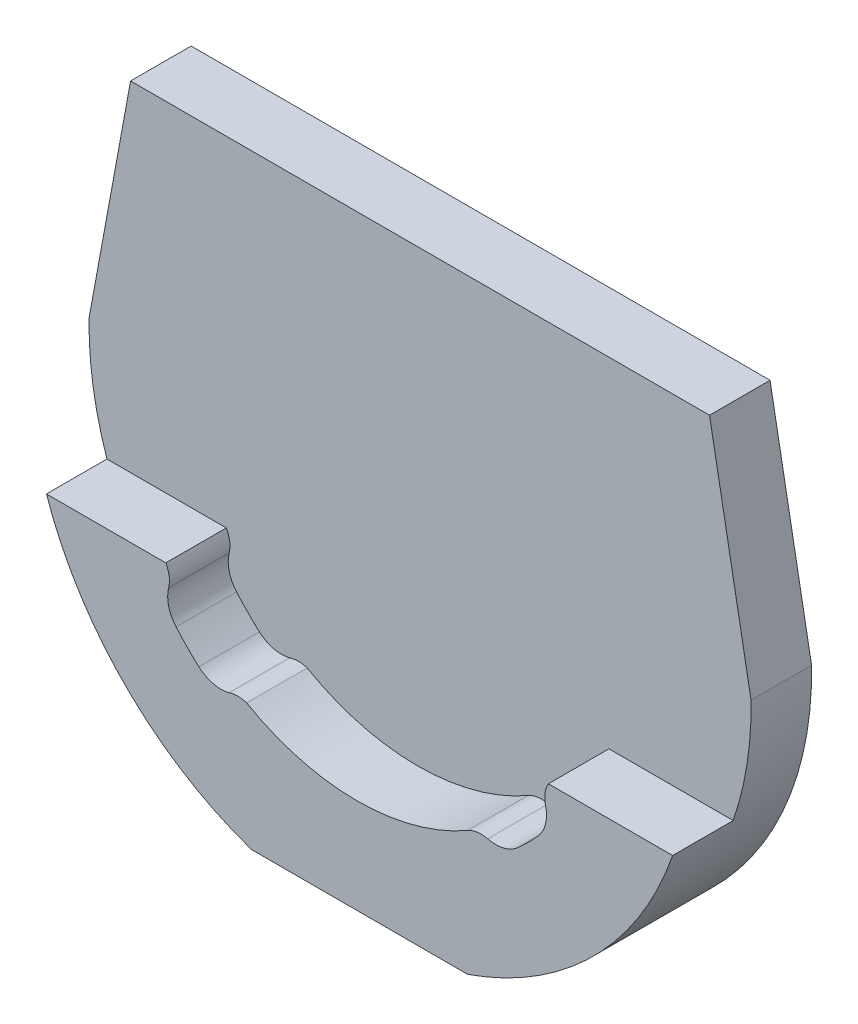
SolidWorks part; units mm, degrees
ref_plane "Front Plane" through (0, 0, 0) normal (0, 0, 1) x (1, 0, 0)
ref_plane "Top Plane" through (0, 0, 0) normal (0, 1, 0) x (1, 0, 0)
ref_plane "Right Plane" through (0, 0, 0) normal (1, 0, 0) x (0, 0, -1)
sketch "Sketch2" plane through (0, 0, 0) normal (0, 0, 1) x (1, 0, 0)
  line L0 (-34.0593, 56.9907) -> (-54.2651, -53.0408)
  line L1 (-24.0734, 56.0031) -> (-44.2734, -53.9969)
  line L2 (24.9266, 56.0031) -> (45.1266, -53.9969)
  line L3 (34.9124, 56.9907) -> (55.1182, -53.0408)
  line L7 (55.1182, -53.0408) -> (44.951, -53.0408)
  line L8 (-44.0979, -53.0408) -> (-54.2651, -53.0408)
  arc A0 (-44.2734, -53.9969) -> (45.1266, -53.9969) centre (0.4266, -53.9969) ccw
  arc A1 (24.9266, 56.0031) -> (-24.0734, 56.0031) centre (0.4266, 56.0031) ccw
  arc A2 (34.9124, 56.9907) -> (-34.0593, 56.9907) centre (0.4266, 56.0031) ccw
  arc A3 (-54.2651, -53.0408) -> (55.1182, -53.0408) centre (0.4266, -53.9969) ccw
extrude "Boss-Extrude1" add sketch "Sketch2" along normal blind 10 contours L2 A1 L1 A0 | L3 A2 L0 L8 L1 A1 L2 L7 | L8 A3 L7 L2 A0 L1
sketch "Sketch4" plane through (0, 0, 10) normal (0, 0, 1) x (1, 0, 0)
  line L1 (-70.8533, -127.1246) -> (76.5167, -127.1246)
  line L2 (-70.8533, -127.1246) -> (-70.8533, -105.6969)
  line L3 (-70.8533, -105.6969) -> (76.5167, -105.6969)
  line L4 (76.5167, -127.1246) -> (76.5167, -105.6969)
  arc A0 (-54.2651, -53.0408) -> (55.1182, -53.0408) centre (0.4266, -53.9969) ccw construction
  point P7 (0.4266, -108.6969)
  dimension "D1" = 3
extrude "Cut-Extrude1" cut sketch "Sketch4" against normal blind 10
sketch "Sketch5" plane through (0, 0, 10) normal (0, 0, 1) x (1, 0, 0)
  line L0 (0.4266, -105.6969) -> (0.4266, -15.6969) construction
  line L1 (18.2927, -105.6969) -> (-17.4396, -105.6969) construction
  line L3 (90.4458, -15.6969) -> (-88.3005, -15.6969)
  line L4 (90.4458, -15.6969) -> (90.4458, 96.6359)
  line L5 (90.4458, 96.6359) -> (-88.3005, 96.6359)
  line L6 (-88.3005, -15.6969) -> (-88.3005, 96.6359)
  dimension "D1" = 90
extrude "Cut-Extrude2" cut sketch "Sketch5" against normal blind 10
sketch "Sketch7" plane through (0, 0, 10) normal (0, 0, 1) x (1, 0, 0)
  line L0 (0.0226, -90.0021) -> (0.4266, -105.6969) construction
  line L1 (18.2927, -105.6969) -> (-17.4396, -105.6969) construction
  line L2 (-31.5873, -71.7521) -> (-51.3117, -71.7521)
  line L3 (31.6325, -71.7521) -> (52.1648, -71.7521)
  line L10 (48.2605, -15.6969) -> (-47.4074, -15.6969)
  line L11 (-47.4074, -15.6969) -> (-54.2651, -53.0408)
  line L12 (-17.4396, -105.6969) -> (18.2927, -105.6969)
  line L13 (55.1182, -53.0408) -> (48.2605, -15.6969)
  line L16 (-17.4396, -105.6969) -> (18.2927, -105.6969)
  arc A5 (-31.1164, -75.0839) -> (-31.5873, -71.7521) centre (-35.4845, -74.0021) ccw
  arc A6 (-31.1164, -75.0839) -> (-29.8908, -80.0575) centre (-25.7777, -76.4061) ccw
  arc A7 (-29.8908, -80.0575) -> (-26.1147, -83.8944) centre (0.4266, -53.9969) ccw
  arc A8 (-26.1147, -83.8944) -> (-21.1411, -85.12) centre (-22.4633, -79.7813) ccw
  arc A9 (-18.2274, -85.112) -> (-21.1411, -85.12) centre (-19.6726, -89.3736) ccw
  arc A10 (-18.2274, -85.112) -> (18.2726, -85.112) centre (0.0226, -53.5021) ccw
  arc A11 (21.6044, -84.6411) -> (18.2726, -85.112) centre (20.5226, -89.0091) ccw
  arc A12 (21.6044, -84.6411) -> (26.578, -83.4155) centre (22.9266, -79.3024) ccw
  arc A13 (26.578, -83.4155) -> (29.936, -80.0575) centre (0.0226, -53.5021) ccw
  arc A14 (29.936, -80.0575) -> (31.3229, -76.4061) centre (25.8229, -76.4061) ccw
  arc A15 (31.3229, -76.4061) -> (31.1616, -75.0839) centre (25.8229, -76.4061) ccw
  arc A16 (31.0296, -74.0021) -> (31.1616, -75.0839) centre (35.5296, -74.0021) ccw
  arc A17 (31.6325, -71.7521) -> (31.0296, -74.0021) centre (35.5296, -74.0021) ccw
  arc A19 (36.5226, -53.5021) -> (36.5213, -53.1965) centre (0.0226, -53.5021) ccw
  arc A30 (-54.2651, -53.0408) -> (-17.4396, -105.6969) centre (0.4266, -53.9969) ccw
  arc A31 (18.2927, -105.6969) -> (55.1182, -53.0408) centre (0.4266, -53.9969) ccw
  arc A32 (-51.3117, -71.7521) -> (-17.4396, -105.6969) centre (0.4266, -53.9969) ccw
  arc A33 (18.2927, -105.6969) -> (52.1648, -71.7521) centre (0.4266, -53.9969) ccw
  point P0 (0, 0)
  arc M3 (-54.2651, -53.0408) -> (-17.4396, -105.6969) centre (0.4266, -53.9969) ccw
  line M4 (-17.4396, -105.6969) -> (18.2927, -105.6969)
  arc M5 (18.2927, -105.6969) -> (55.1182, -53.0408) centre (0.4266, -53.9969) ccw
  dimension "D1" = 15.7
  dimension "D2" = 0
extrude "Boss-Extrude2" add sketch "Sketch7" along normal blind 10 contours A10 L0 L16 L3 A17 A16 A15 A14 A13 A12 A11 M5 | L0 A10 A9 A8 A7 A6 A5 L2 M3 M4
